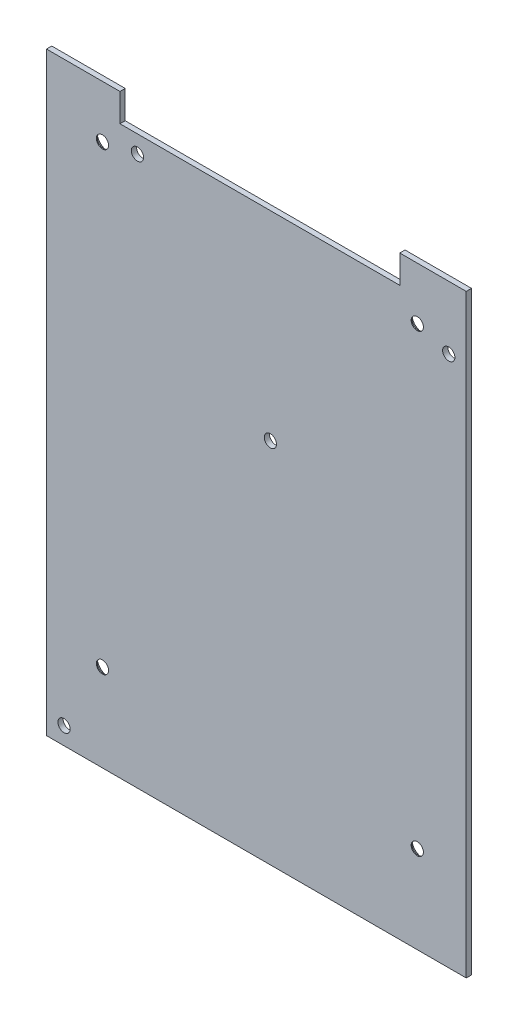
SolidWorks part; units mm, degrees
ref_plane "Спереди" through (0, 0, 0) normal (0, 0, 1) x (1, 0, 0)
ref_plane "Сверху" through (0, 0, 0) normal (0, 1, 0) x (1, 0, 0)
ref_plane "Справа" through (0, 0, 0) normal (1, 0, 0) x (0, 0, -1)
sketch "Эскиз1" plane through (0, 0, 0) normal (0, 0, 1) x (1, 0, 0)
  line L1 (0, 0) -> (135, 0)
  line L2 (0, 0) -> (0, 73)
  line L3 (0, 73) -> (135, 73)
  line L4 (135, 0) -> (135, 73)
  circle A0 centre (118, 55) radius 1.75
  circle A1 centre (29, 60) radius 1.75
  circle A2 centre (67, 8) radius 1.75
  dimension "D3" = 17
  dimension "D4" = 18
  dimension "D5" = 3.5
  dimension "D6" = 13
  dimension "D7" = 89
  dimension "D8" = 52
  dimension "D12" = 38
  dimension "D1" = 73
  dimension "D2" = 135
extrude "Вытянуть1" add sketch "Эскиз1" along normal blind 1.5
sketch "Эскиз2" plane through (0, 0, 0) normal (0, 0, -1) x (-1, 0, 0)
  line L0 (-135, 0) -> (-135, 73) construction
  line L1 (-135, 0) -> (-135, 73)
  line L2 (0, 0) -> (-135, 0) construction
  line L3 (0, 0) -> (-135, 0)
  line L4 (0, 73) -> (0, 0) construction
  line L5 (0, 73) -> (0, 0)
  line L6 (0, 73) -> (12.5, 73)
  line L7 (12.5, 73) -> (12.5, -77)
  line L8 (12.5, -77) -> (-137.5, -77)
  line L9 (-137.5, -77) -> (-137.5, 73)
  line L10 (-137.5, 73) -> (-135, 73)
  line L11 (-135, 73) -> (0, 73) construction
  dimension "D1" = 2.5
  dimension "D2" = 12.5
  dimension "D3" = 150
extrude "Вытянуть2" add sketch "Эскиз2" against normal up to surface (1.5 mm away) up to face at (30.75, 60, 1.5)
sketch "Эскиз3" plane through (0, 0, 0) normal (0, 0, -1) x (-1, 0, 0)
  line L2 (-137.5, 73) -> (12.5, 73) construction
  circle A0 centre (-109, 58) radius 1.75
  circle A1 centre (-109, -72) radius 1.75
  circle A2 centre (-19, -72) radius 1.75
  circle A3 centre (-19, 58) radius 1.75
  circle A4 centre (-29, 60) radius 1.75 construction
  dimension "D4" = 15
  dimension "D5" = 15
  dimension "D6" = 90
  dimension "D7" = 130
  dimension "D8" = 130
  dimension "D9" = 3.5
  dimension "D1" = 90
  dimension "D2" = 10
  dimension "D3" = 10
extrude "Вырез-Вытянуть1" cut sketch "Эскиз3" against normal blind 10
sketch "Эскиз4" plane through (0, 0, 0) normal (0, 0, -1) x (-1, 0, 0)
  line L0 (-137.5, 73) -> (12.5, 73) construction
  line L1 (-3, -92.7324) -> (38.775, -92.7324)
  line L2 (-3, -92.7324) -> (-3, 81.8205)
  line L3 (-3, 81.8205) -> (38.775, 81.8205)
  line L4 (38.775, -92.7324) -> (38.775, 81.8205)
  line L5 (-148.1985, -96.7927) -> (-123, -96.7927)
  line L6 (-148.1985, -96.7927) -> (-148.1985, 81.8205)
  line L7 (-148.1985, 81.8205) -> (-123, 81.8205)
  line L8 (-123, -96.7927) -> (-123, 81.8205)
  line L9 (-104, 77.924) -> (-24, 77.924)
  line L10 (-104, 77.924) -> (-104, 65)
  line L11 (-104, 65) -> (-24, 65)
  line L12 (-24, 77.924) -> (-24, 65)
  circle A0 centre (-19, 58) radius 1.75 construction
  circle A1 centre (-118, 55) radius 1.75 construction
  circle A3 centre (-109, 58) radius 1.75 construction
  dimension "D1" = 16
  dimension "D3" = 8
  dimension "D5" = 5
  dimension "D2" = 5
  dimension "D4" = 178.6133
  dimension "D6" = 5
extrude "Вырез-Вытянуть2" cut sketch "Эскиз4" against normal blind 10
sketch "Эскиз5" plane through (0, -77, 0) normal (0, -1, 0) x (1, 0, 0)
  line L4 (123, 0) -> (123, 1.5)
  line L5 (123, 1.5) -> (3, 1.5)
  line L6 (3, 1.5) -> (3, 0)
  line L7 (3, 0) -> (123, 0)
  line L8 (123, 0) -> (123, 1.5)
  line L9 (123, 1.5) -> (3, 1.5)
  line L10 (3, 1.5) -> (3, 0)
  line L11 (3, 0) -> (123, 0)
  dimension "D1" = 0
extrude "Вытянуть3" add sketch "Эскиз5" along normal blind 20
sketch "Эскиз6" plane through (0, 0, 0) normal (0, 0, -1) x (-1, 0, 0)
  line L1 (-3, -97) -> (-123, -97) construction
  line L2 (-3, 73) -> (-3, -97) construction
  circle A0 centre (-8, -92) radius 1.75
  circle A1 centre (-109, -72) radius 1.75 construction
  dimension "D1" = 5
  dimension "D2" = 5
extrude "Вырез-Вытянуть3" cut sketch "Эскиз6" against normal blind 20
chamfer "Фаска1" distance 1.25 angle 45 4 edges at (17.25, -72, 0) (107.25, -72, 0) (17.25, 58, 0) (107.25, 58, 0)
